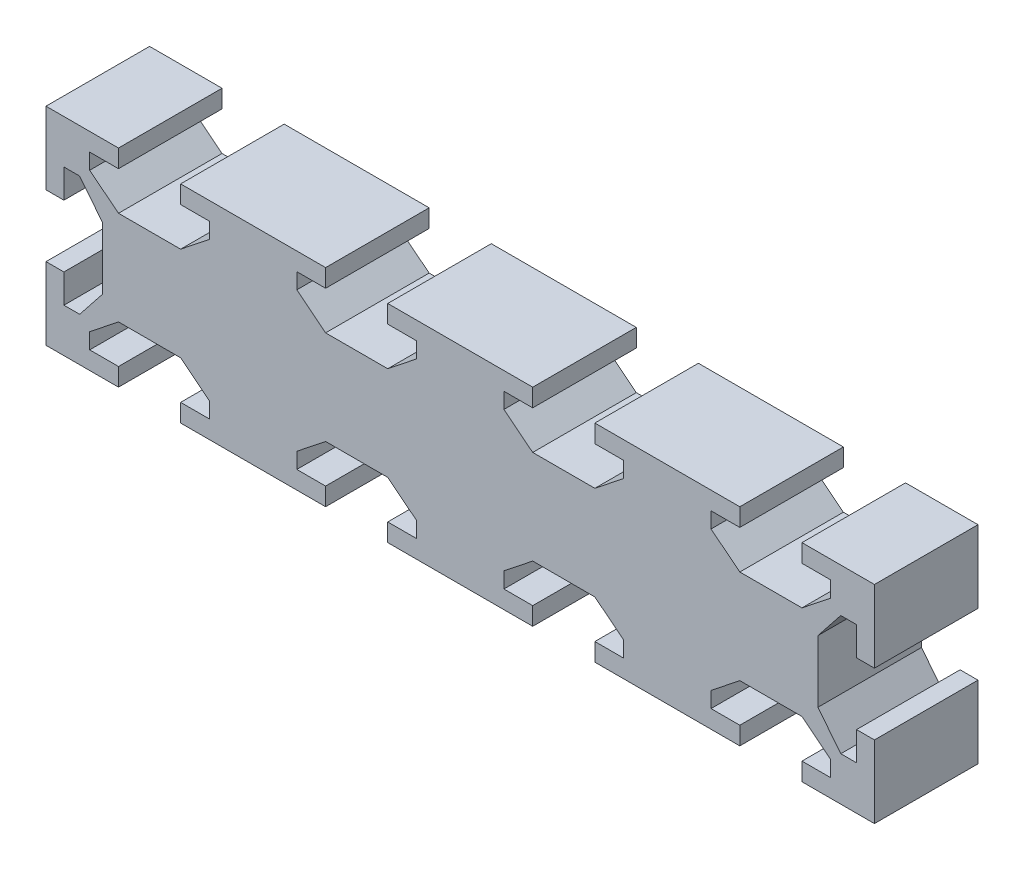
SolidWorks part; units mm, degrees
ref_plane "Front Plane" through (0, 0, 0) normal (0, 0, 1) x (1, 0, 0)
ref_plane "Top Plane" through (0, 0, 0) normal (0, 1, 0) x (1, 0, 0)
ref_plane "Right Plane" through (0, 0, 0) normal (1, 0, 0) x (0, 0, -1)
sketch "Sketch1" plane through (0, 0, 0) normal (0, 0, 1) x (1, 0, 0)
  line L0 (-10, 3) -> (-10, 10)
  line L1 (-10, 10) -> (-3, 10)
  line L2 (-3, 10) -> (-3, 8.27)
  line L3 (-10, 3) -> (-8.27, 3)
  line L4 (-3, 8.27) -> (-5.78, 8.27)
  line L5 (-8.27, 3) -> (-8.27, 5.78)
  line L6 (-5.78, 8.27) -> (-5.78, 6.75)
  line L7 (-8.27, 5.78) -> (-6.75, 5.78)
  line L8 (-5.78, 6.75) -> (-3, 4.5423)
  line L9 (-6.75, 5.78) -> (-4.5423, 3)
  line L10 (-3, 4.5423) -> (3, 4.5423)
  line L11 (-4.5423, 3) -> (-4.5423, -3)
  line L12 (0, 0) -> (-4.5423, 0) construction
  line L13 (-3, -4.5423) -> (3, -4.5423)
  line L14 (-6.75, -5.78) -> (-4.5423, -3)
  line L15 (-5.78, -6.75) -> (-3, -4.5423)
  line L16 (-8.27, -5.78) -> (-6.75, -5.78)
  line L17 (-5.78, -8.27) -> (-5.78, -6.75)
  line L18 (-8.27, -3) -> (-8.27, -5.78)
  line L19 (-3, -8.27) -> (-5.78, -8.27)
  line L20 (-10, -3) -> (-8.27, -3)
  line L21 (-3, -10) -> (-3, -8.27)
  line L22 (-10, -10) -> (-3, -10)
  line L23 (-10, -3) -> (-10, -10)
  line L24 (0, 4.5423) -> (0, -4.5423) construction
  line L25 (5.78, 6.75) -> (3, 4.5423)
  line L26 (5.78, 8.27) -> (5.78, 6.75)
  line L27 (5.78, -6.75) -> (3, -4.5423)
  line L28 (5.78, -8.27) -> (5.78, -6.75)
  line L29 (3, -8.27) -> (5.78, -8.27)
  line L30 (3, 8.27) -> (5.78, 8.27)
  line L31 (10, -10) -> (3, -10)
  line L32 (3, -10) -> (3, -8.27)
  line L33 (3, 10) -> (3, 8.27)
  line L34 (10, 10) -> (3, 10)
  line L35 (17, 10) -> (17, 8.27)
  line L36 (17, 8.27) -> (14.22, 8.27)
  line L37 (14.22, 8.27) -> (14.22, 6.75)
  line L38 (14.22, 6.75) -> (17, 4.5423)
  line L39 (17, 4.5423) -> (23, 4.5423)
  line L40 (17, -4.5423) -> (23, -4.5423)
  line L41 (14.22, -6.75) -> (17, -4.5423)
  line L42 (14.22, -8.27) -> (14.22, -6.75)
  line L43 (17, -8.27) -> (14.22, -8.27)
  line L44 (17, -10) -> (17, -8.27)
  line L45 (25.78, 6.75) -> (23, 4.5423)
  line L46 (25.78, 8.27) -> (25.78, 6.75)
  line L47 (25.78, -6.75) -> (23, -4.5423)
  line L48 (25.78, -8.27) -> (25.78, -6.75)
  line L49 (23, -8.27) -> (25.78, -8.27)
  line L50 (23, 8.27) -> (25.78, 8.27)
  line L51 (30, -10) -> (23, -10)
  line L52 (23, -10) -> (23, -8.27)
  line L53 (23, 10) -> (23, 8.27)
  line L54 (30, 10) -> (23, 10)
  line L55 (30, 10) -> (30, -10) construction
  line L56 (10, -10) -> (17, -10)
  line L57 (10, 10) -> (17, 10)
  line L58 (37, 10) -> (37, 8.27)
  line L59 (37, 8.27) -> (34.22, 8.27)
  line L60 (34.22, 8.27) -> (34.22, 6.75)
  line L61 (34.22, 6.75) -> (37, 4.5423)
  line L62 (37, 4.5423) -> (43, 4.5423)
  line L63 (37, -4.5423) -> (43, -4.5423)
  line L64 (34.22, -6.75) -> (37, -4.5423)
  line L65 (34.22, -8.27) -> (34.22, -6.75)
  line L66 (37, -8.27) -> (34.22, -8.27)
  line L67 (37, -10) -> (37, -8.27)
  line L68 (45.78, 6.75) -> (43, 4.5423)
  line L69 (45.78, 8.27) -> (45.78, 6.75)
  line L70 (45.78, -6.75) -> (43, -4.5423)
  line L71 (45.78, -8.27) -> (45.78, -6.75)
  line L72 (43, -8.27) -> (45.78, -8.27)
  line L73 (43, 8.27) -> (45.78, 8.27)
  line L74 (50, -10) -> (43, -10)
  line L75 (43, -10) -> (43, -8.27)
  line L76 (43, 10) -> (43, 8.27)
  line L77 (50, 10) -> (43, 10)
  line L78 (70, 10) -> (70, 3)
  line L79 (30, -10) -> (37, -10)
  line L80 (30, 10) -> (37, 10)
  line L81 (57, 10) -> (57, 8.27)
  line L82 (57, 8.27) -> (54.22, 8.27)
  line L83 (54.22, 8.27) -> (54.22, 6.75)
  line L84 (54.22, 6.75) -> (57, 4.5423)
  line L85 (57, 4.5423) -> (63, 4.5423)
  line L86 (57, -4.5423) -> (63, -4.5423)
  line L87 (54.22, -6.75) -> (57, -4.5423)
  line L88 (54.22, -8.27) -> (54.22, -6.75)
  line L89 (57, -8.27) -> (54.22, -8.27)
  line L90 (57, -10) -> (57, -8.27)
  line L91 (65.78, 6.75) -> (63, 4.5423)
  line L92 (65.78, 8.27) -> (65.78, 6.75)
  line L93 (65.78, -6.75) -> (63, -4.5423)
  line L94 (65.78, -8.27) -> (65.78, -6.75)
  line L95 (63, -8.27) -> (65.78, -8.27)
  line L96 (63, 8.27) -> (65.78, 8.27)
  line L97 (70, -10) -> (63, -10)
  line L98 (63, -10) -> (63, -8.27)
  line L99 (63, 10) -> (63, 8.27)
  line L100 (70, 10) -> (63, 10)
  line L101 (70, 3) -> (68.27, 3)
  line L102 (50, -10) -> (57, -10)
  line L103 (50, 10) -> (57, 10)
  line L104 (20, 0) -> (15.4577, 0) construction
  line L105 (40, 0) -> (35.4577, 0) construction
  line L106 (60, 0) -> (55.4577, 0) construction
  line L107 (68.27, 3) -> (68.27, 5.78)
  line L108 (68.27, 5.78) -> (66.75, 5.78)
  line L109 (66.75, 5.78) -> (64.5423, 3)
  line L110 (64.5423, 3) -> (64.5423, -3)
  line L111 (64.5423, -3) -> (66.75, -5.78)
  line L112 (66.75, -5.78) -> (68.27, -5.78)
  line L113 (68.27, -5.78) -> (68.27, -3)
  line L114 (68.27, -3) -> (70, -3)
  line L115 (70, -3) -> (70, -10)
  dimension "D1" = 7
  dimension "D2" = 1.73
  dimension "D3" = 2.78
  dimension "D4" = 10
  dimension "D5" = 10
  dimension "D6" = 1.52
  dimension "D7" = 3.55
  dimension "D8" = 3
  dimension "D9" = 3
  dimension "D10" = 3
  dimension "D12" = 17
  dimension "D11" = 4
extrude "Boss-Extrude1" add sketch "Sketch1" along normal mid plane 10
